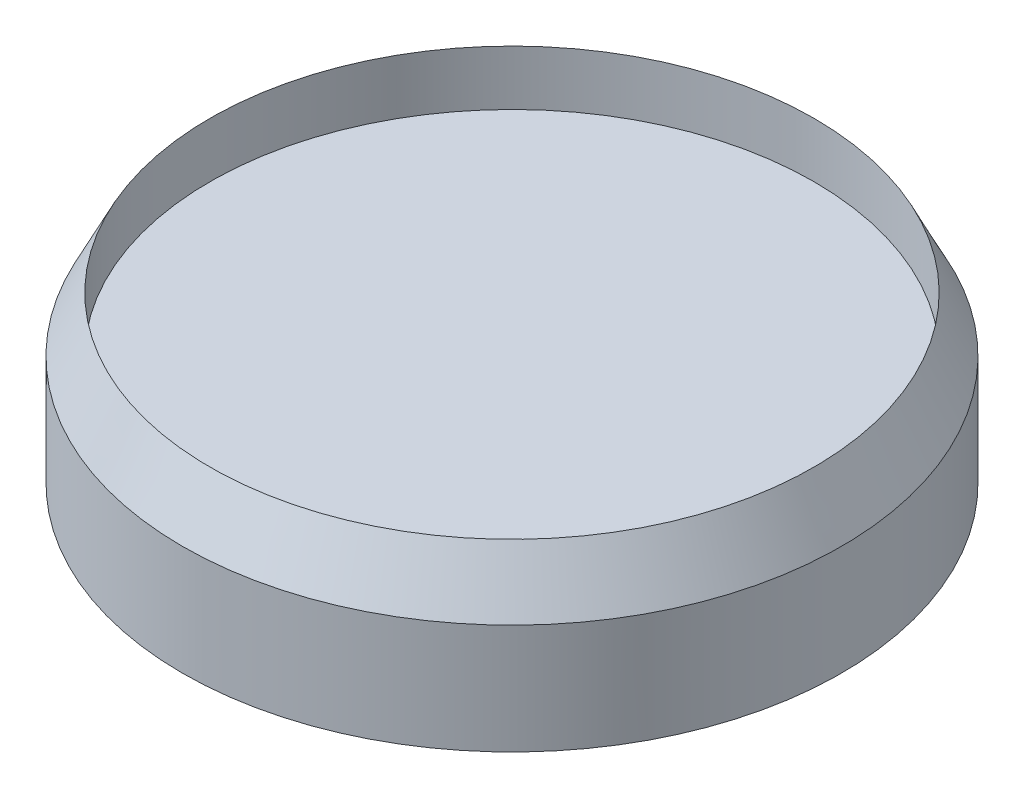
SolidWorks part; units mm, degrees
ref_plane "Front Plane" through (0, 0, 0) normal (0, 0, 1) x (1, 0, 0)
ref_plane "Top Plane" through (0, 0, 0) normal (0, 1, 0) x (1, 0, 0)
ref_plane "Right Plane" through (0, 0, 0) normal (1, 0, 0) x (0, 0, -1)
sketch "Sketch1" plane through (0, 0, 0) normal (0, 1, 0) x (1, 0, 0)
  circle A0 centre (0, 0) radius 30
extrude "Boss-Extrude1" add sketch "Sketch1" along normal blind 10
sketch "Sketch2" plane through (0, 10, 0) normal (0, 1, 0) x (1, 0, 0)
  circle A0 centre (0, 0) radius 27.5
sketch "Sketch3" plane through (0, 0, 0) normal (0, 0, 1) x (1, 0, 0)
  line L0 (0, 10) -> (-27.5, 10) construction
  line L2 (-27.5, 10) -> (-27.5, 15)
  line L3 (-27.5, 15) -> (-30, 10)
  line L4 (-30, 10) -> (-27.5, 10)
  line L5 (0, 10) -> (0, 29.9986) construction
  point P10 (0, 0)
revolve "Revolve1" add sketch "Sketch3" angle 360 about L5
